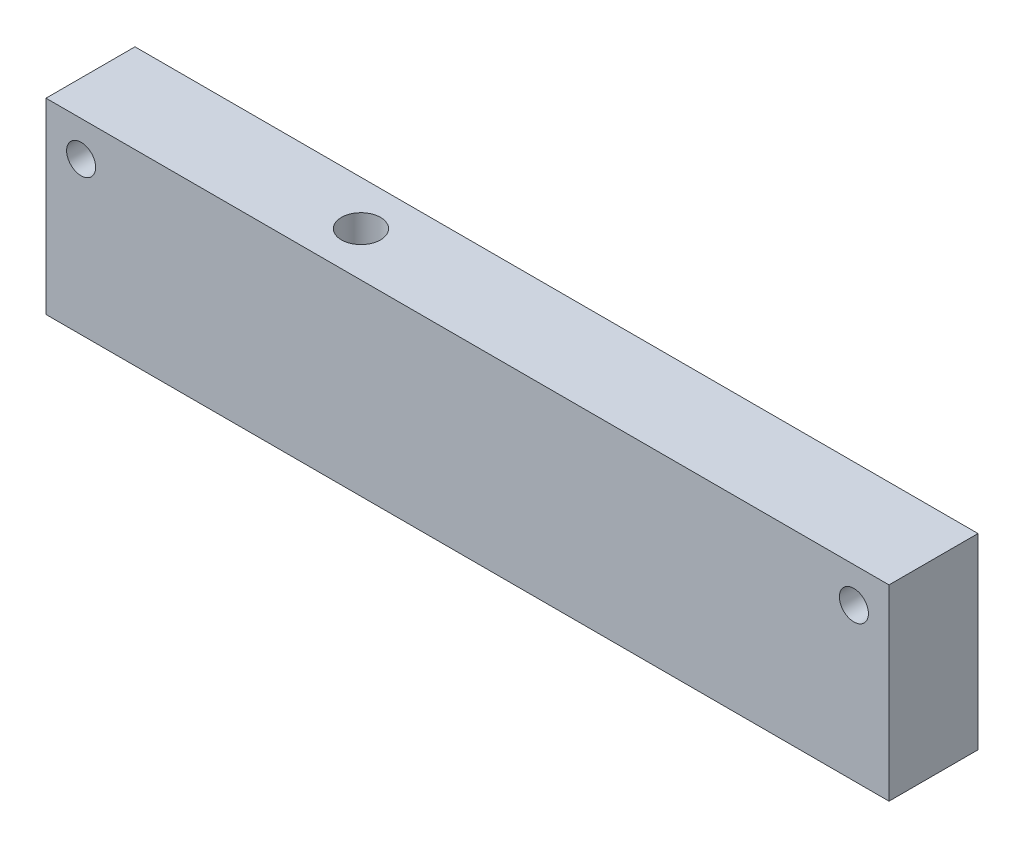
SolidWorks part; units mm, degrees
ref_plane "Front Plane" through (0, 0, 0) normal (0, 0, 1) x (1, 0, 0)
ref_plane "Top Plane" through (0, 0, 0) normal (0, 1, 0) x (1, 0, 0)
ref_plane "Right Plane" through (0, 0, 0) normal (1, 0, 0) x (0, 0, -1)
sketch "Sketch1" plane through (0, 0, 0) normal (0, 1, 0) x (1, 0, 0)
  line L0 (-90, 0) -> (90, 0) construction
  line L1 (-90, -9.5) -> (90, -9.5)
  line L2 (-90, -9.5) -> (-90, 9.5)
  line L3 (-90, 9.5) -> (90, 9.5)
  line L4 (90, -9.5) -> (90, 9.5)
  line L5 (-90, -9.5) -> (90, 9.5) construction
  line L6 (-90, 9.5) -> (90, -9.5) construction
  circle A0 centre (-82.5, 0) radius 3.1
  circle A1 centre (82.5, 0) radius 3.1
  circle A2 centre (-32.25, 0) radius 4.175
  point P0 (0, 0)
  dimension "D1" = 8.35
  dimension "D2" = 6.2
  dimension "D3" = 6.2
  dimension "D4" = 7.5
  dimension "D5" = 50.25
  dimension "D6" = 9.5
  dimension "D7" = 7.5
  dimension "D8" = 165
extrude "Boss-Extrude1" add sketch "Sketch1" along normal blind 20
sketch "Sketch2" plane through (0, 20, 0) normal (0, 1, 0) x (1, 0, 0)
  line L1 (-90, 9.5) -> (90, 9.5)
  line L2 (-90, 9.5) -> (-90, -9.5)
  line L3 (-90, -9.5) -> (90, -9.5)
  line L4 (90, 9.5) -> (90, -9.5)
  circle A0 centre (-32.25, 0) radius 4.175
  dimension "D1" = 8.35
extrude "Boss-Extrude3" add sketch "Sketch2" along normal blind 20
sketch "Sketch3" plane through (0, 0, 9.5) normal (0, 0, 1) x (1, 0, 0)
  line L0 (-90, 32.5) -> (90, 32.5) construction
  line L1 (-90, 40) -> (-90, 0) construction
  line L2 (90, 40) -> (90, 0) construction
  line L3 (-90, 40) -> (90, 40) construction
  circle A0 centre (-82.5, 32.5) radius 3.1
  circle A1 centre (82.5, 32.5) radius 3.1
  dimension "D2" = 6.2
  dimension "D3" = 6.2
  dimension "D5" = 7.5
  dimension "D1" = 7.5
  dimension "D4" = 7.5
extrude "Cut-Extrude1" cut sketch "Sketch3" against normal blind 20
sketch "Sketch4" plane through (0, 0, -9.5) normal (0, 0, -1) x (-1, 0, 0)
  line L0 (-90, 40) -> (90, 40) construction
  line L1 (-72.5, 32.5) -> (19.5, 32.5)
  line L2 (-72.5, 32.5) -> (-72.5, 7.5)
  line L3 (-72.5, 7.5) -> (19.5, 7.5)
  line L4 (19.5, 32.5) -> (19.5, 7.5)
  line L5 (44.5, 32.5) -> (72.5, 32.5)
  line L6 (44.5, 32.5) -> (44.5, 7.5)
  line L7 (44.5, 7.5) -> (72.5, 7.5)
  line L8 (72.5, 32.5) -> (72.5, 7.5)
  line L9 (-90, 0) -> (90, 0) construction
  circle A0 centre (-82.5, 32.5) radius 3.1
  circle A1 centre (82.5, 32.5) radius 3.1
  dimension "D1" = 6.2
  dimension "D2" = 6.2
  dimension "D3" = 7.5
  dimension "D4" = 7.5
  dimension "D5" = 10
  dimension "D6" = 25
  dimension "D7" = 7.5
  dimension "D8" = 0
  dimension "D9" = 10
  dimension "D10" = 28
extrude "Boss-Extrude4" add sketch "Sketch4" against normal blind 9.8 contours A0
